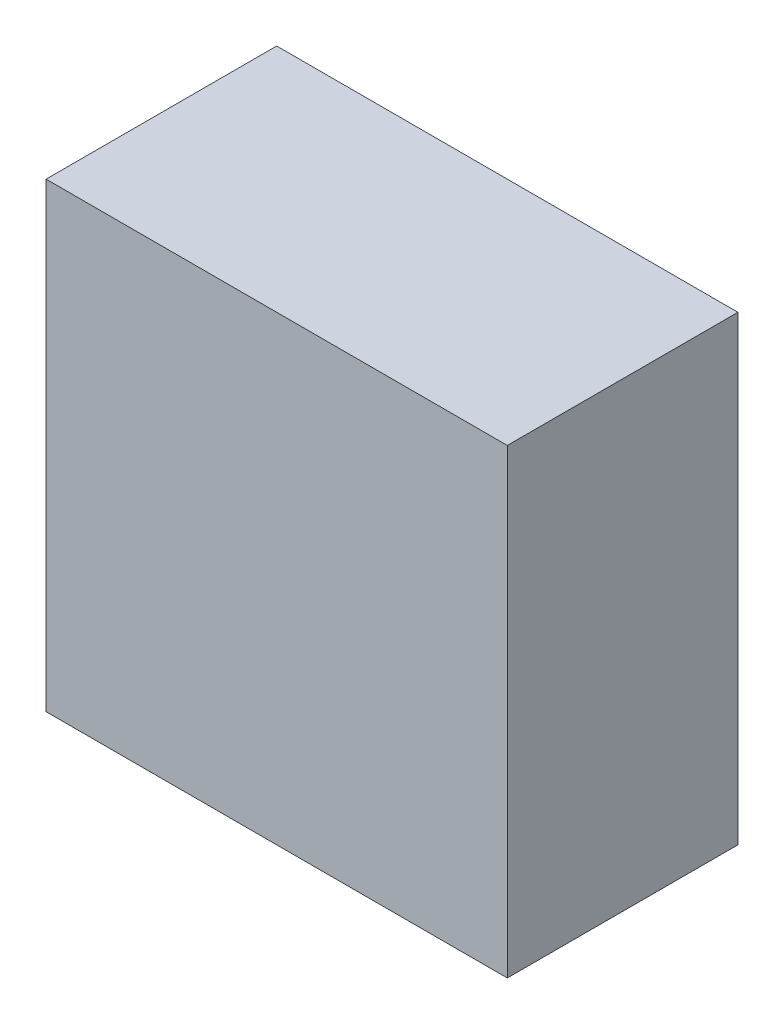
SolidWorks part; units mm, degrees
ref_plane "Přední rovina" through (0, 0, 0) normal (0, 0, 1) x (1, 0, 0)
ref_plane "Horní rovina" through (0, 0, 0) normal (0, 1, 0) x (1, 0, 0)
ref_plane "Pravá rovina" through (0, 0, 0) normal (1, 0, 0) x (0, 0, -1)
sketch "Skica1" plane through (0, 0, 0) normal (0, 0, 1) x (1, 0, 0)
  line L1 (-10, -10) -> (10, -10)
  line L2 (-10, -10) -> (-10, 10)
  line L3 (-10, 10) -> (10, 10)
  line L4 (10, -10) -> (10, 10)
  line L5 (-10, -10) -> (10, 10) construction
  line L6 (-10, 10) -> (10, -10) construction
  point P0 (0, 0)
  dimension "D1" = 20
  dimension "D2" = 20
extrude "Přidat vysunutím1" add sketch "Skica1" along normal blind 10
sketch "Skica2" plane through (0, 0, 0) normal (0, 0, -1) x (-1, 0, 0)
  line L1 (-8.5, -8.5) -> (8.5, -8.5)
  line L2 (-8.5, -8.5) -> (-8.5, 8.5)
  line L3 (-8.5, 8.5) -> (8.5, 8.5)
  line L4 (8.5, -8.5) -> (8.5, 8.5)
  line L5 (-8.5, -8.5) -> (8.5, 8.5) construction
  line L6 (-8.5, 8.5) -> (8.5, -8.5) construction
  point P0 (0, 0)
  dimension "D1" = 17
  dimension "D2" = 17
extrude "Odebrat vysunutím1" cut sketch "Skica2" against normal blind 7.5
sketch "Skica3" plane through (0, 0, 7.5) normal (0, 0, -1) x (-1, 0, 0)
  circle A0 centre (0, 0) radius 2.65
  dimension "D1" = 5.3
extrude "Přidat vysunutím2" add sketch "Skica3" along normal blind 7.5
sketch "Skica4" plane through (0, 0, 0) normal (0, 0, -1) x (-1, 0, 0)
  line L0 (-0.7, 2.15) -> (0.7, 2.15)
  line L1 (0.7, 2.15) -> (0.7, 0.7)
  line L2 (0.7, 0.7) -> (2.15, 0.7)
  line L3 (2.15, 0.7) -> (2.15, -0.7)
  line L4 (0, 0) -> (0, 2.65) construction
  line L5 (-2.15, 0.7) -> (-2.15, -0.7)
  line L6 (-0.7, 0.7) -> (-2.15, 0.7)
  line L7 (-0.7, 2.15) -> (-0.7, 0.7)
  line L8 (0, 0) -> (2.65, 0) construction
  line L9 (0.7, -0.7) -> (2.15, -0.7)
  line L10 (0.7, -2.15) -> (0.7, -0.7)
  line L11 (-0.7, -2.15) -> (0.7, -2.15)
  line L12 (-0.7, -2.15) -> (-0.7, -0.7)
  line L13 (-0.7, -0.7) -> (-2.15, -0.7)
  circle A0 centre (0, 0) radius 2.65 construction
  circle A1 centre (0, 0) radius 2.65 construction
  point P15 (0, 2.15)
  point P19 (2.15, 0)
  point P24 (-2.15, 0)
  dimension "D1" = 0.7
  dimension "D2" = 0.7
  dimension "D3" = 2.15
  dimension "D4" = 2.15
extrude "Odebrat vysunutím2" cut sketch "Skica4" against normal blind 7.5
